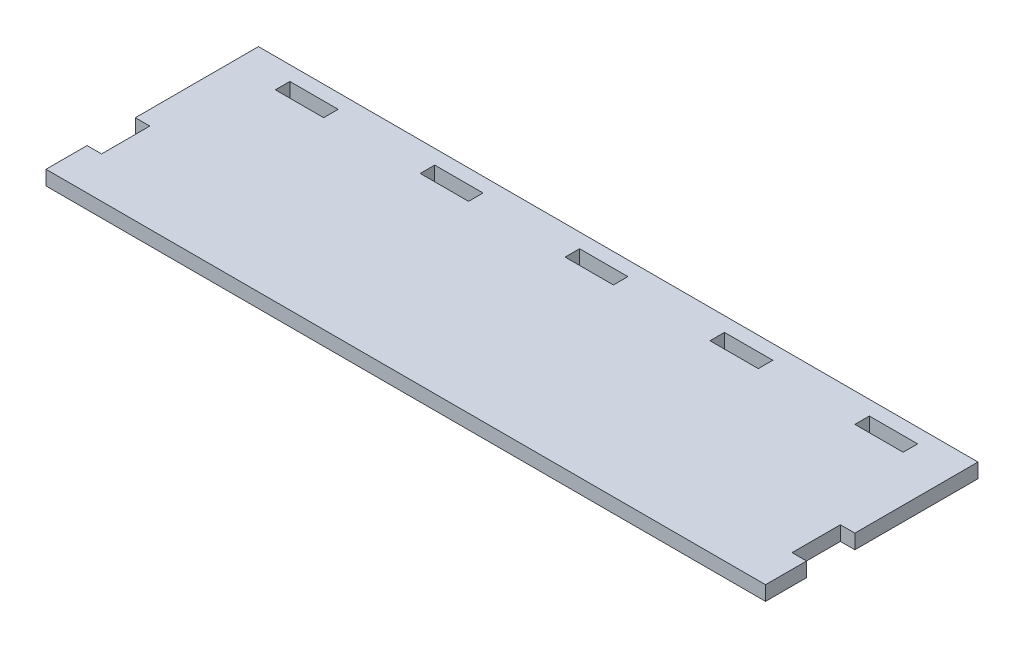
SolidWorks part; units mm, degrees
ref_plane "Front Plane" through (0, 0, 0) normal (0, 0, 1) x (1, 0, 0)
ref_plane "Top Plane" through (0, 0, 0) normal (0, 1, 0) x (1, 0, 0)
ref_plane "Right Plane" through (0, 0, 0) normal (1, 0, 0) x (0, 0, -1)
sketch "Sketch1" plane through (0, 0, 0) normal (0, 1, 0) x (1, 0, 0)
  line L32 (-74.5, 44) -> (74.5, 44)
  line L33 (-74.5, 44) -> (-74.5, 18.5)
  line L34 (-74.5, 0) -> (74.5, 0)
  line L35 (74.5, 44) -> (74.5, 18.5)
  line L36 (-5, 41) -> (5, 41)
  line L37 (-5, 41) -> (-5, 38)
  line L38 (-5, 38) -> (5, 38)
  line L39 (5, 41) -> (5, 38)
  line L40 (25, 41) -> (35, 41)
  line L41 (25, 41) -> (25, 38)
  line L42 (25, 38) -> (35, 38)
  line L43 (35, 41) -> (35, 38)
  line L44 (55, 41) -> (65, 41)
  line L45 (55, 41) -> (55, 38)
  line L46 (55, 38) -> (65, 38)
  line L47 (65, 41) -> (65, 38)
  line L48 (-65, 41) -> (-65, 38)
  line L49 (-55, 38) -> (-65, 38)
  line L50 (-55, 41) -> (-55, 38)
  line L51 (-55, 41) -> (-65, 41)
  line L52 (-35, 41) -> (-35, 38)
  line L53 (-25, 38) -> (-35, 38)
  line L54 (-25, 41) -> (-25, 38)
  line L55 (-25, 41) -> (-35, 41)
  line L56 (71.5, 18.5) -> (74.5, 18.5)
  line L57 (71.5, 18.5) -> (71.5, 8.5)
  line L58 (71.5, 8.5) -> (74.5, 8.5)
  line L59 (-71.5, 8.5) -> (-74.5, 8.5)
  line L60 (-71.5, 18.5) -> (-71.5, 8.5)
  line L61 (-71.5, 18.5) -> (-74.5, 18.5)
  line L62 (-74.5, 8.5) -> (-74.5, 0)
  line L63 (74.5, 8.5) -> (74.5, 0)
  point P0 (73, 8.5)
  point P1 (0, 0)
  point P2 (0, 38)
  dimension "D2" = 20
  dimension "D3" = 10
  dimension "D4" = 38
  dimension "D11" = 149
  dimension "D12" = 3
  dimension "D13" = 3
  dimension "D14" = 10
  dimension "D15" = 3
  dimension "D16" = 10
  dimension "D17" = 8.5
  dimension "D18" = 20
extrude "Boss-Extrude1" add sketch "Sketch1" along normal blind 3
